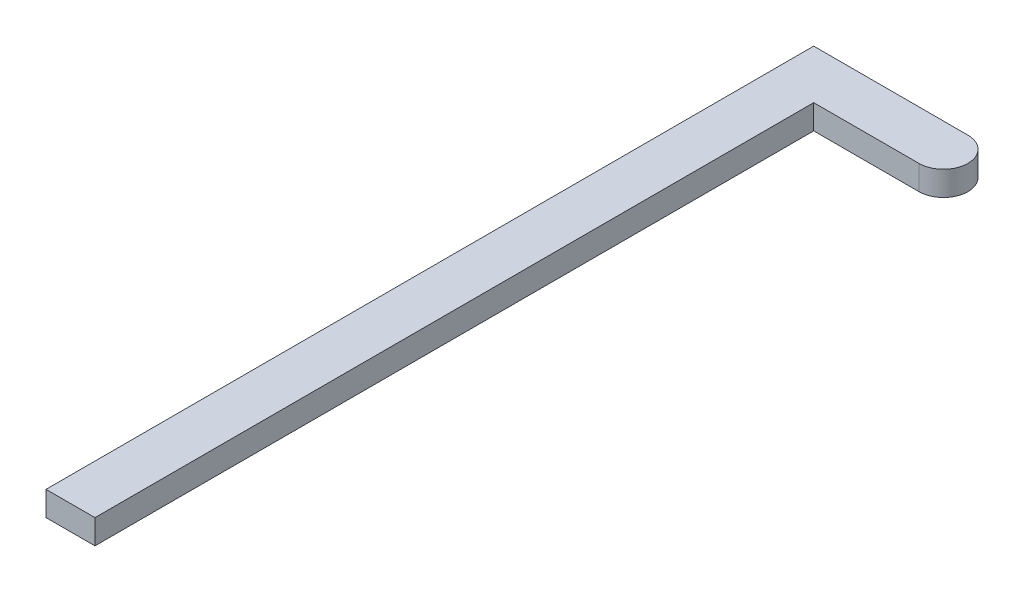
SolidWorks part; units mm, degrees
ref_plane "Front Plane" through (0, 0, 0) normal (0, 0, 1) x (1, 0, 0)
ref_plane "Top Plane" through (0, 0, 0) normal (0, 1, 0) x (1, 0, 0)
ref_plane "Right Plane" through (0, 0, 0) normal (1, 0, 0) x (0, 0, -1)
sketch "Sketch1" plane through (0, 0, 0) normal (0, 1, 0) x (1, 0, 0)
  line L0 (0, 0) -> (-33.65, 0) construction
  line L1 (-33.65, 0) -> (-33.65, -192.786) construction
  line L2 (0, 6.35) -> (-40, 6.35)
  line L3 (-40, 6.35) -> (-40, -192.786)
  line L4 (0, -6.35) -> (-27.3, -6.35)
  line L5 (-27.3, -6.35) -> (-27.3, -192.786)
  line L6 (-40, -192.786) -> (-27.3, -192.786)
  arc A0 (0, 6.35) -> (0, -6.35) centre (0, 0) cw
  dimension "D1" = 192.786
  dimension "D2" = 40
  dimension "D3" = 6.35
  dimension "D4" = 6.35
extrude "Boss-Extrude1" add sketch "Sketch1" along normal blind 6.35
